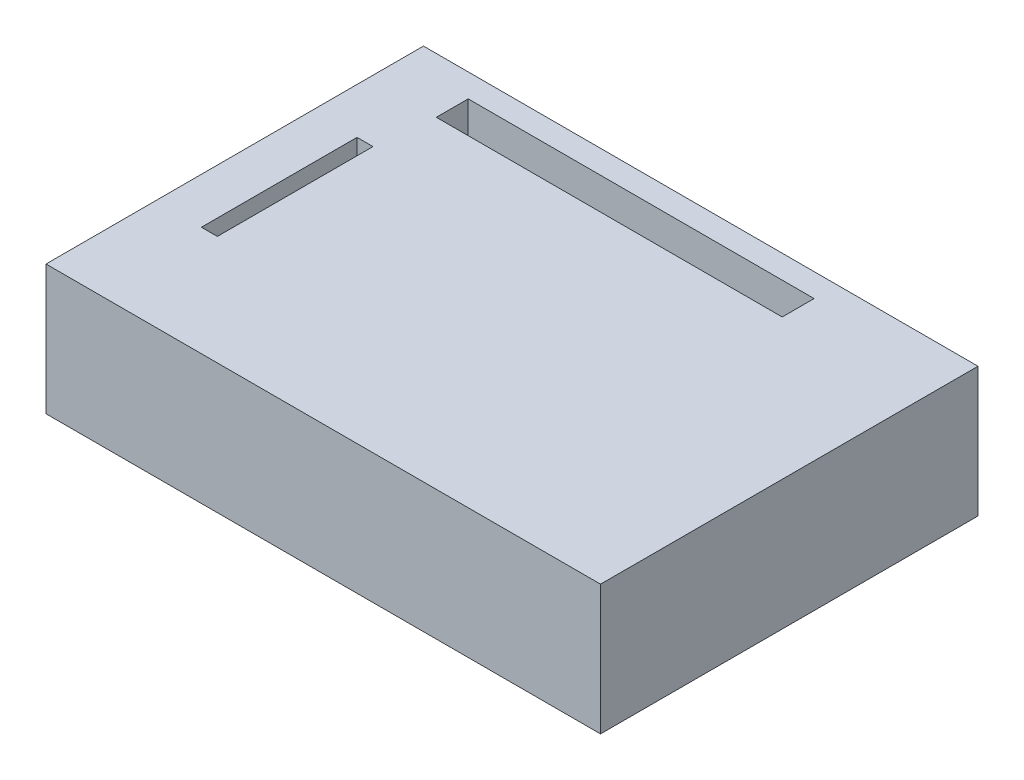
SolidWorks part; units mm, degrees
ref_plane "Front" through (0, 0, 0) normal (0, 0, 1) x (1, 0, 0)
ref_plane "Top" through (0, 0, 0) normal (0, 1, 0) x (1, 0, 0)
ref_plane "Right" through (0, 0, 0) normal (1, 0, 0) x (0, 0, -1)
sketch "Sketch1" plane through (0, 0, 0) normal (0, 1, 0) x (1, 0, 0)
  line L1 (0, 0) -> (85.5, 0)
  line L2 (0, 0) -> (0, -58.2)
  line L3 (0, -58.2) -> (85.5, -58.2)
  line L4 (85.5, 0) -> (85.5, -58.2)
  line L5 (7.07, -17.31) -> (9.53, -17.31)
  line L6 (7.07, -17.31) -> (7.07, -41.31)
  line L7 (7.07, -41.31) -> (9.53, -41.31)
  line L8 (9.53, -17.31) -> (9.53, -41.31)
  line L9 (10.5, -3.6) -> (63.83, -3.6)
  line L10 (10.5, -3.6) -> (10.5, -8.52)
  line L11 (10.5, -8.52) -> (63.83, -8.52)
  line L12 (63.83, -3.6) -> (63.83, -8.52)
  point P9 (7.07, -29.31)
  point P10 (8.3, -17.31)
  point P15 (10.5, -6.06)
  point P16 (37.165, -3.6)
  dimension "D1" = 85.5
  dimension "D2" = 58.2
  dimension "D3" = 2.46
  dimension "D4" = 7.07
  dimension "D5" = 17.31
  dimension "D6" = 24
  dimension "D7" = 53.33
  dimension "D8" = 4.92
  dimension "D9" = 10.5
  dimension "D10" = 3.6
extrude "Boss-Extrude1" add sketch "Sketch1" along normal blind 20
